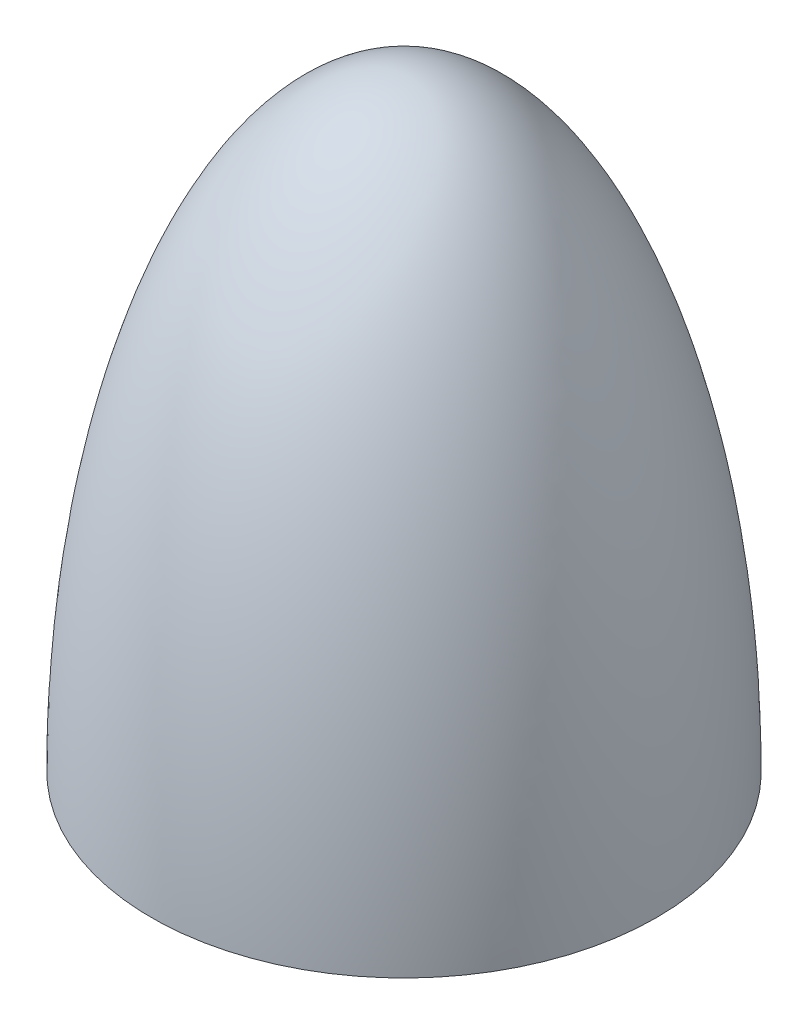
SolidWorks part; units mm, degrees
ref_plane "Front Plane" through (0, 0, 0) normal (0, 0, 1) x (1, 0, 0)
ref_plane "Top Plane" through (0, 0, 0) normal (0, 1, 0) x (1, 0, 0)
ref_plane "Right Plane" through (0, 0, 0) normal (1, 0, 0) x (0, 0, -1)
sketch "Sketch4" plane through (0, 0, 0) normal (0, 0, 1) x (1, 0, 0)
  line L0 (59.7, 0) -> (60.9, 0)
  line L1 (60.9, 0) -> (59.7, 0)
  line L2 (0, 0) -> (0, 145.2)
  line L5 (-59.7, 0) -> (-60.9, 0)
  ellipse E0 centre (0, 0) end of major axis (0, 144) minor radius 59.7 (59.7, 0) -> (0, 144) ccw
  spline S1 degree 3 poles (60.9, 0) (60.9, 18.913) (57.782, 56.7389) (46.666, 96.8743) (34.4132, 121.1274) (23.8677, 134.7387) (12.282, 143.2432) (4.094, 145.2) (0, 145.2) knots 4.712389 4.712389 4.712389 4.712389 5.105088 5.497787 5.694137 5.890486 6.086836 6.283185 6.283185 6.283185 6.283185
revolve "Revolve7" add sketch "Sketch4" angle 360 about L2
